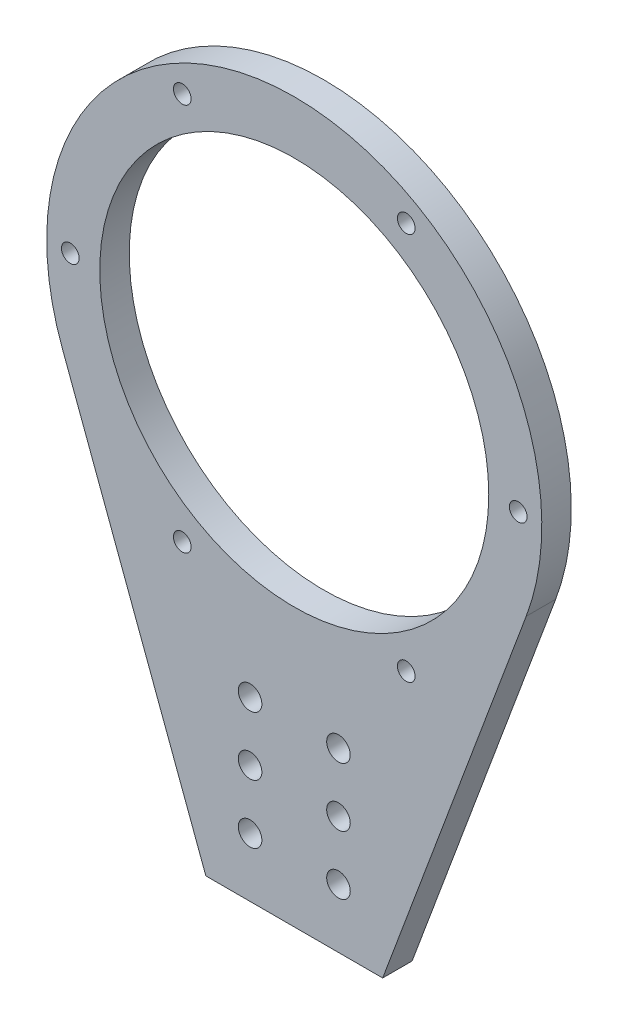
SolidWorks part; units mm, degrees
material "Acrylic (Medium-high impact)"
ref_plane "Front Plane" through (0, 0, 0) normal (0, 0, 1) x (1, 0, 0)
ref_plane "Top Plane" through (0, 0, 0) normal (0, 1, 0) x (1, 0, 0)
ref_plane "Right Plane" through (0, 0, 0) normal (1, 0, 0) x (0, 0, -1)
sketch "Sketch1" plane through (0, 0, 0) normal (0, 0, 1) x (1, 0, 0)
  line L0 (0, 0) -> (0, -75.7544) construction
  line L1 (-15, -80) -> (15, -80)
  line L4 (15, -80) -> (39.3543, -14.6711)
  line L5 (-15, -80) -> (-39.3543, -14.6711)
  line L6 (-39.3543, -14.6711) -> (0, 0) construction
  line L7 (0, 0) -> (39.3543, -14.6711) construction
  circle A0 centre (0, 0) radius 33
  circle A1 centre (0, 0) radius 42
  arc A2 (-39.3543, -14.6711) -> (39.3543, -14.6711) centre (0, 0) ccw
  dimension "D1" = 30
  dimension "D2" = 84
  dimension "D3" = 66
  dimension "D4" = 80
  dimension "D6" = 15
extrude "Boss-Extrude1" add sketch "Sketch1" along normal blind 5
sketch "Sketch9" plane through (0, 0, 5) normal (0, 0, 1) x (1, 0, 0)
  line L0 (60.1553, 0) -> (-60.1553, 0) construction
  line L1 (-60.1553, 0) -> (0, 0) construction
  line L2 (0, 0) -> (27.4803, 47.5973) construction
  line L3 (27.4803, 47.5973) -> (-28.626, -49.5817) construction
  line L4 (-28.626, -49.5817) -> (0, 0) construction
  line L5 (-29.2217, 50.6135) -> (0, 0) construction
  line L6 (0, 0) -> (29.2328, -50.6327) construction
  circle A0 centre (0, 0) radius 38 construction
  circle A1 centre (19, 32.909) radius 1.5
  circle A2 centre (38, 0) radius 1.5
  circle A3 centre (19, -32.909) radius 1.5
  circle A4 centre (-19, -32.909) radius 1.5
  circle A5 centre (-38, 0) radius 1.5
  circle A6 centre (-19, 32.909) radius 1.5
  dimension "D1" = 60
  dimension "D2" = 60
extrude "Cut-Extrude5" cut sketch "Sketch9" against normal blind 7
sketch "Sketch10" plane through (0, 0, 5) normal (0, 0, 1) x (1, 0, 0)
  line L0 (0, 0) -> (0, -98.5039) construction
  line L2 (-15, -80) -> (15, -80) construction
  circle A1 centre (7.5, -60) radius 2
  circle A2 centre (7.5, -70) radius 2
  circle A3 centre (-7.5, -70) radius 2
  circle A4 centre (-7.5, -60) radius 2
  circle A6 centre (0, 0) radius 37.5 construction
  circle A7 centre (-7.5, -50) radius 2
  circle A8 centre (7.5, -50) radius 2
  dimension "D2" = 10
  dimension "D3" = 7.5
  dimension "D4" = 7.5
  dimension "D5" = 7.5
  dimension "D6" = 7.5
  dimension "D7" = 10
  dimension "D8" = 10
  dimension "D9" = 10
  dimension "D10" = 10
  dimension "D11" = 10
extrude "Cut-Extrude6" cut sketch "Sketch10" against normal blind 7
